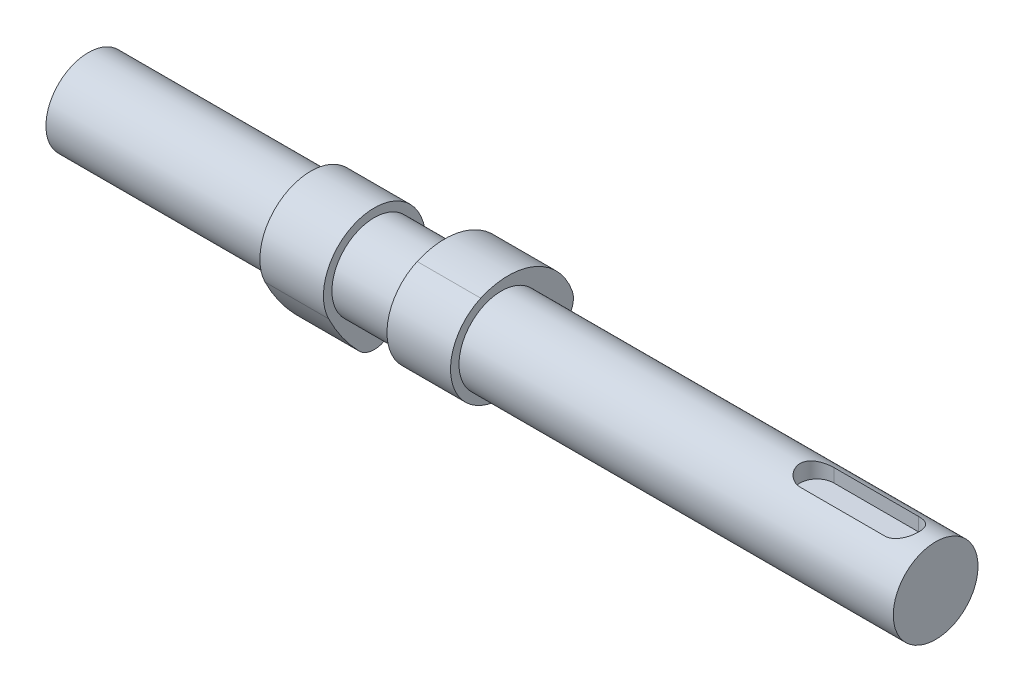
SolidWorks part; units mm, degrees
ref_plane "Front Plane" through (0, 0, 0) normal (0, 0, 1) x (1, 0, 0)
ref_plane "Top Plane" through (0, 0, 0) normal (0, 1, 0) x (1, 0, 0)
ref_plane "Right Plane" through (0, 0, 0) normal (1, 0, 0) x (0, 0, -1)
sketch "Sketch1" plane through (0, 0, 0) normal (1, 0, 0) x (0, 0, -1)
  circle A0 centre (0, 0) radius 10
  dimension "D1" = 20
extrude "Boss-Extrude1" add sketch "Sketch1" against normal blind 75 and the other way blind 125
sketch "Sketch2" plane through (0, 0, 0) normal (1, 0, 0) x (0, 0, -1)
  line L0 (0, 0) -> (11.997, 0) construction
  arc A0 (-4.8671, 10.9687) -> (5.3062, -10.7631) centre (0, 0) ccw
  arc A1 (15.4795, -3.5877) -> (16.7127, 1.6619) centre (11.997, 0) ccw
  arc A2 (-4.8671, 10.9687) -> (16.7127, 1.6619) centre (1.6224, -3.6562) cw
  arc A3 (5.3062, -10.7631) -> (15.4795, -3.5877) centre (-12.3812, 25.1139) ccw
  dimension "D1" = 24
  dimension "D2" = 10
  dimension "D3" = 16
  dimension "D4" = 40
  dimension "D5" = 12.5
extrude "Boss-Extrude4" add sketch "Sketch2" along normal mid plane 15 from offset 15 separate body
mirror "Mirror9" about plane through (0, 0, 0) normal (1, 0, 0) of bodies 107
move or copy body "Body-Move/Copy2" bodies to move or copy 108 copy no rotation origin (0, 0, 0) rotation axis (-1, 0, 0) rotation angle 90 parameters "Angle Around Edge"=90
ref_plane "Plane1" through (0, 10, 0) normal (0, 1, 0) x (1, 0, 0)
sketch "Sketch3" plane through (0, 10, 0) normal (0, 1, 0) x (1, 0, 0)
  line L0 (125, 0) -> (89, 0) construction
  line L1 (125, -10) -> (125, 10) construction
  line L2 (97, 0) -> (117, 0) construction
  line L3 (97, 4) -> (117, 4)
  line L4 (97, -4) -> (117, -4)
  arc A0 (97, 4) -> (97, -4) centre (97, 0) ccw
  arc A1 (117, -4) -> (117, 4) centre (117, 0) ccw
  point P7 (107, 0)
  dimension "D3" = 4
  dimension "D1" = 20
  dimension "D2" = 8
extrude "Cut-Extrude1" cut sketch "Sketch3" against normal blind 4
